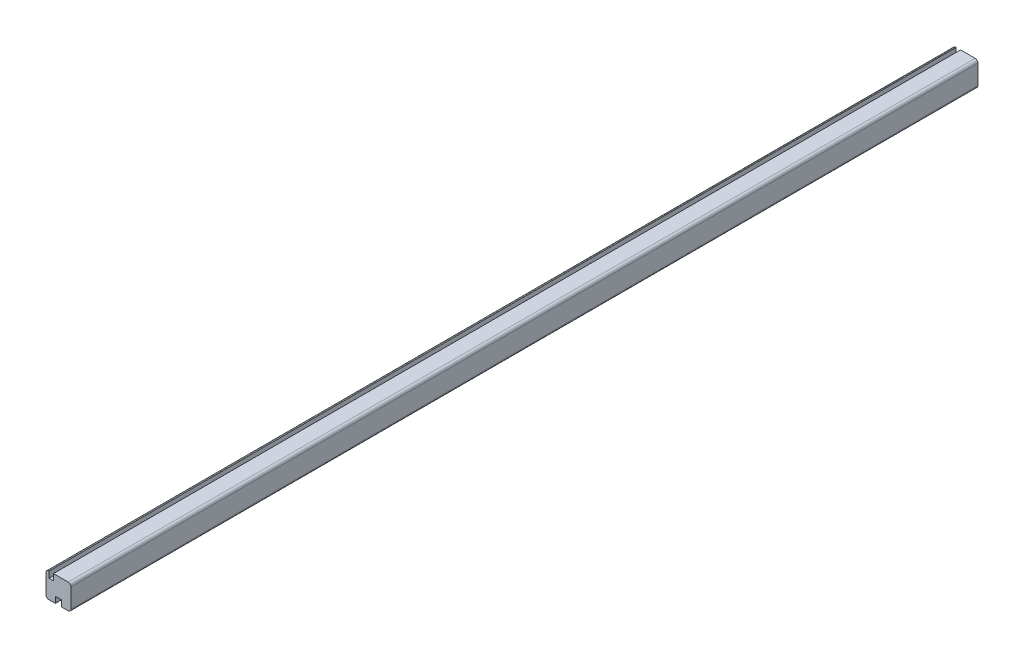
SolidWorks part; units mm, degrees
ref_plane "Front Plane" through (0, 0, 0) normal (0, 0, 1) x (1, 0, 0)
ref_plane "Top Plane" through (0, 0, 0) normal (0, 1, 0) x (1, 0, 0)
ref_plane "Right Plane" through (0, 0, 0) normal (1, 0, 0) x (0, 0, -1)
sketch "Sketch1" plane through (0, 0, 0) normal (0, 0, 1) x (1, 0, 0)
  line L0 (0, 0) -> (0, -50000) construction
  line L1 (-15.5, -20) -> (-5, -20)
  line L2 (-20, -15.5) -> (-20, 15.5)
  line L3 (-15.5, 20) -> (-15, 20)
  line L4 (20, -15.5) -> (20, 15.5)
  line L5 (-20, -20) -> (20, 20) construction
  line L6 (-20, 20) -> (20, -20) construction
  line L8 (-5, -20) -> (-5, -10)
  line L9 (-5, -10) -> (5, -10)
  line L10 (5, -20) -> (5, -10)
  line L12 (-15, 20) -> (-15, 10)
  line L13 (-15, 10) -> (-8, 10)
  line L14 (-8, 20) -> (-8, 10)
  line L15 (5, -20) -> (15.5, -20)
  line L16 (-8, 20) -> (15.5, 20)
  arc A0 (-20, 15.5) -> (-15.5, 20) centre (-15.5, 15.5) cw
  arc A1 (-15.5, -20) -> (-20, -15.5) centre (-15.5, -15.5) cw
  arc A2 (15.5, -20) -> (20, -15.5) centre (15.5, -15.5) ccw
  arc A3 (15.5, 20) -> (20, 15.5) centre (15.5, 15.5) cw
  point P0 (0, 0)
  dimension "D8" = 4.5
  dimension "D1" = 40
  dimension "D2" = 40
  dimension "D3" = 15
  dimension "D4" = 10
  dimension "D5" = 5
  dimension "D6" = 28
  dimension "D7" = 10
extrude "Boss-Extrude1" add sketch "Sketch1" along normal blind 1455
